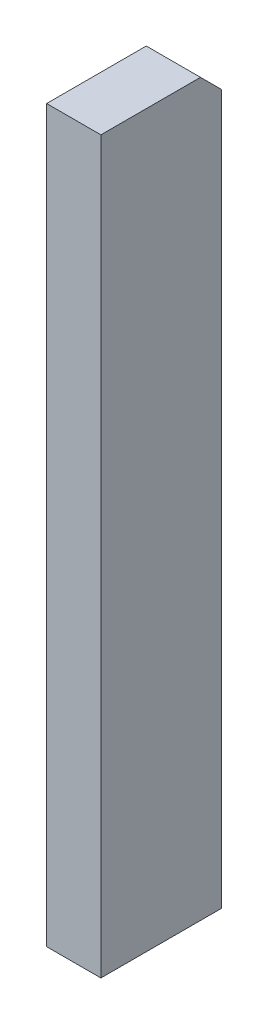
SolidWorks part; units mm, degrees
ref_plane "Front Plane" through (0, 0, 0) normal (0, 0, 1) x (1, 0, 0)
ref_plane "Top Plane" through (0, 0, 0) normal (0, 1, 0) x (1, 0, 0)
ref_plane "Right Plane" through (0, 0, 0) normal (1, 0, 0) x (0, 0, -1)
sketch "Sketch1" plane through (0, 0, 0) normal (0, 0, 1) x (1, 0, 0)
  line L1 (0, 0) -> (2.6, 0)
  line L2 (0, 0) -> (0, 35)
  line L3 (0, 35) -> (2.6, 35)
  line L4 (2.6, 0) -> (2.6, 35)
extrude "Boss-Extrude1" add sketch "Sketch1" along normal blind 5.775
chamfer "Chamfer1" distance 1 angle 45 1 edges at (1.3, 35, 0)
